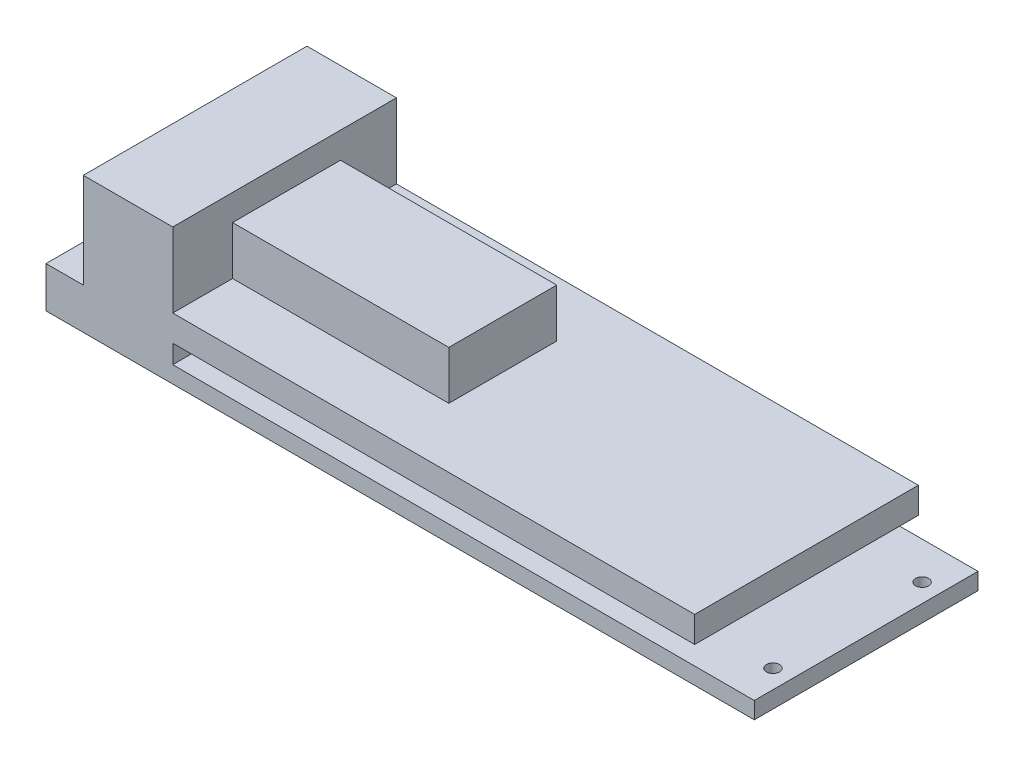
SolidWorks part; units mm, degrees
ref_plane "Front Plane" through (0, 0, 0) normal (0, 0, 1) x (1, 0, 0)
ref_plane "Top Plane" through (0, 0, 0) normal (0, 1, 0) x (1, 0, 0)
ref_plane "Right Plane" through (0, 0, 0) normal (1, 0, 0) x (0, 0, -1)
sketch "Sketch1" plane through (0, 0, 0) normal (0, 1, 0) x (1, 0, 0)
  line L0 (90, 6.4433) -> (90, -49993.5567) construction
  line L1 (-95, 30) -> (95, 30)
  line L2 (-95, 30) -> (-95, -30)
  line L3 (-95, -30) -> (95, -30)
  line L4 (95, 30) -> (95, -30)
  line L5 (-95, 30) -> (95, -30) construction
  line L6 (-95, -30) -> (95, 30) construction
  line L7 (40.8763, -20) -> (50040.8763, -20) construction
  line L8 (52.2165, 20) -> (50052.2165, 20) construction
  circle A0 centre (90, -20) radius 1.75
  circle A1 centre (90, 20) radius 1.75
  point P0 (0, 0)
  dimension "D6" = 3.5
  dimension "D1" = 190
  dimension "D2" = 60
  dimension "D3" = 5
  dimension "D4" = 10
  dimension "D5" = 10
extrude "Boss-Extrude1" add sketch "Sketch1" along normal blind 4.5
sketch "Sketch2" plane through (0, 4.5, 0) normal (0, 1, 0) x (1, 0, 0)
  line L0 (-95, -30) -> (95, -30) construction
  line L1 (-95, 30) -> (-85, 30)
  line L2 (-95, 30) -> (-95, -30)
  line L3 (-95, -30) -> (-85, -30)
  line L4 (-85, 30) -> (-85, -30)
  dimension "D1" = 10
extrude "Boss-Extrude2" add sketch "Sketch2" along normal blind 6.5
sketch "Sketch3" plane through (0, 4.5, 0) normal (0, 1, 0) x (1, 0, 0)
  line L0 (-85, -30) -> (-85, 30) construction
  line L1 (-85, 30) -> (-61, 30)
  line L2 (-85, 30) -> (-85, -30)
  line L3 (-85, -30) -> (-61, -30)
  line L4 (-61, 30) -> (-61, -30)
  line L5 (95, 30) -> (-85, 30) construction
  line L6 (-85, -30) -> (95, -30) construction
  dimension "D1" = 24
extrude "Boss-Extrude3" add sketch "Sketch3" along normal blind 32
ref_plane "Plane1" through (0, 19, 0) normal (0, 1, 0) x (1, 0, 0)
sketch "Sketch5" plane through (0, 19, 0) normal (0, 1, 0) x (1, 0, 0)
  line L0 (-74.2268, -0.4191) -> (-74.2268, 12.0809) construction
  line L2 (-74.2268, 12.0809) -> (-94.2268, 12.0809)
  line L3 (-74.2268, 12.0809) -> (-74.2268, -12.9191)
  line L4 (-74.2268, -12.9191) -> (-94.2268, -12.9191)
  line L5 (-94.2268, 12.0809) -> (-94.2268, -12.9191)
  dimension "D1" = 12.5
  dimension "D2" = 25
  dimension "D3" = 20
extrude "Boss-Extrude4" add sketch "Sketch5" along normal blind 7
ref_plane "Plane2" through (0, 9.5, 0) normal (0, 1, 0) x (1, 0, 0)
sketch "Sketch6" plane through (0, 9.5, 0) normal (0, 1, 0) x (1, 0, 0)
  line L0 (-61, -30) -> (95, -30) construction
  line L1 (-61, 30) -> (79, 30)
  line L2 (-61, 30) -> (-61, -30)
  line L3 (-61, -30) -> (79, -30)
  line L4 (79, 30) -> (79, -30)
  dimension "D1" = 140
extrude "Boss-Extrude5" add sketch "Sketch6" along normal blind 7
sketch "Sketch7" plane through (0, 16.5, 0) normal (0, 1, 0) x (1, 0, 0)
  line L0 (-61, 0) -> (-61, 15) construction
  line L1 (-61, 30) -> (-61, -30) construction
  line L3 (-61, 15) -> (-3, 15)
  line L4 (-61, 15) -> (-61, -13.9538)
  line L5 (-61, -13.9538) -> (-3, -13.9538)
  line L6 (-3, 15) -> (-3, -13.9538)
  dimension "D1" = 15
  dimension "D2" = 58
extrude "Boss-Extrude6" add sketch "Sketch7" along normal blind 13
sketch "Sketch8" plane through (0, 0, 0) normal (0, -1, 0) x (1, 0, 0)
  line L0 (-89, 11.8532) -> (-89, 50011.8532) construction
  line L1 (-96.8274, 20) -> (49903.1726, 20) construction
  line L2 (-96.6774, -20) -> (49903.3226, -20) construction
  line L3 (-95, -30) -> (-95, 30) construction
  line L4 (-95, 30) -> (95, 30) construction
  line L5 (95, -30) -> (-95, -30) construction
  circle A0 centre (-89, -20) radius 1.75
  circle A1 centre (-89, 19.9555) radius 1.75
  dimension "D4" = 3.5
  dimension "D1" = 6
  dimension "D2" = 10
  dimension "D3" = 10
extrude "Cut-Extrude1" cut sketch "Sketch8" against normal blind 13
